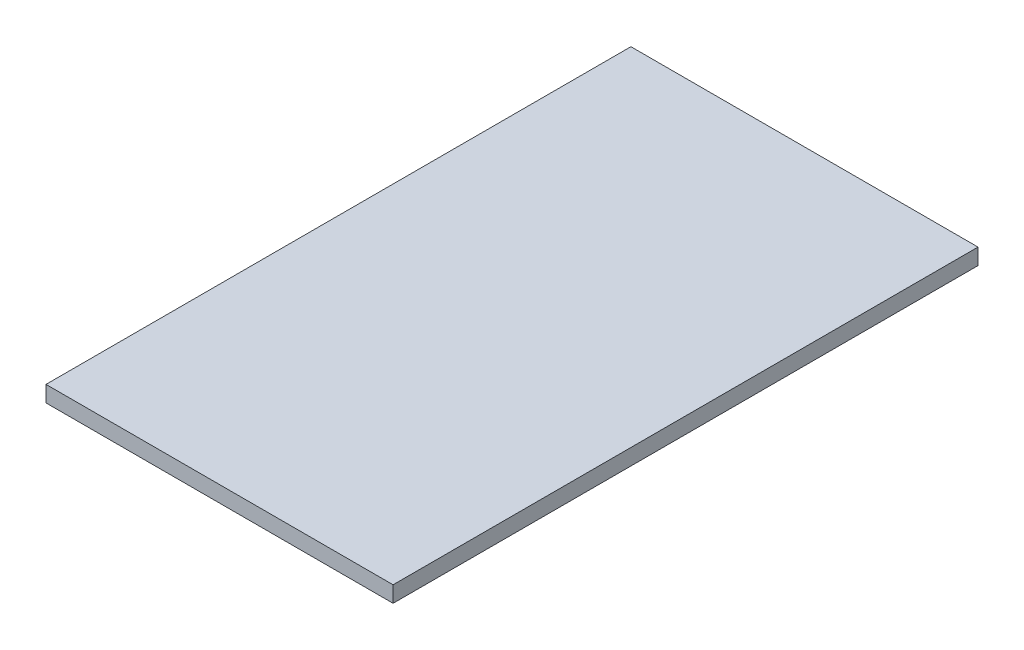
SolidWorks part; units mm, degrees
ref_plane "Front Plane" through (0, 0, 0) normal (0, 0, 1) x (1, 0, 0)
ref_plane "Top Plane" through (0, 0, 0) normal (0, 1, 0) x (1, 0, 0)
ref_plane "Right Plane" through (0, 0, 0) normal (1, 0, 0) x (0, 0, -1)
sketch "Sketch1" plane through (0, 0, 0) normal (0, 1, 0) x (1, 0, 0)
  line L1 (-27, 45.5) -> (27, 45.5)
  line L2 (-27, 45.5) -> (-27, -45.5)
  line L3 (-27, -45.5) -> (27, -45.5)
  line L4 (27, 45.5) -> (27, -45.5)
  line L5 (-27, 45.5) -> (27, -45.5) construction
  line L6 (-27, -45.5) -> (27, 45.5) construction
  point P0 (0, 0)
extrude "Boss-Extrude1" add sketch "Sketch1" along normal blind 2.5
